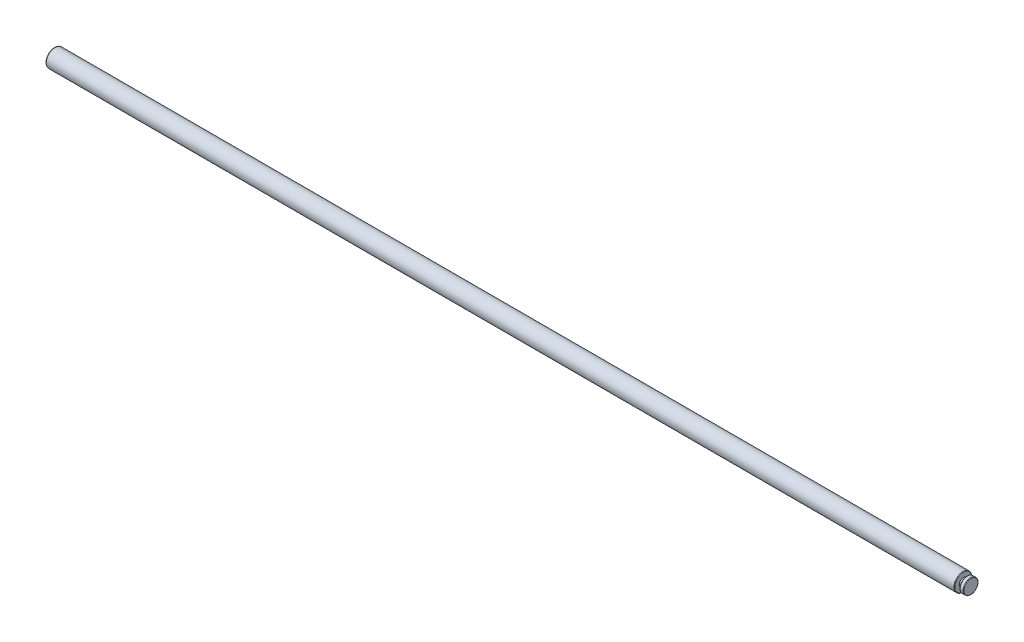
SolidWorks part; units mm, degrees
ref_plane "Front Plane" through (0, 0, 0) normal (0, 0, 1) x (1, 0, 0)
ref_plane "Top Plane" through (0, 0, 0) normal (0, 1, 0) x (1, 0, 0)
ref_plane "Right Plane" through (0, 0, 0) normal (1, 0, 0) x (0, 0, -1)
sketch "Sketch1" plane through (0, 0, 0) normal (0, 0, 1) x (1, 0, 0)
  line L0 (0, 34.9364) -> (0, -34.4273) construction
  line L1 (-72.6727, 0) -> (73.8182, 0) construction
  line L2 (177, 6.5441) -> (177, -8.583) construction
  line L3 (-180, 0) -> (180, 0)
  line L4 (-180, 0) -> (-180, 3.5)
  line L5 (-180, 3.5) -> (177, 3.5)
  line L6 (180, 0) -> (180, 2.9)
  line L7 (177, 3.5) -> (177, 1.5)
  line L8 (177, 1.5) -> (178.5, 1.5)
  line L9 (178.5, 1.5) -> (178.5, 2.9)
  line L10 (178.5, 2.9) -> (180, 2.9)
  dimension "D1" = 3.5
  dimension "D2" = 360
  dimension "D3" = 3
  dimension "D4" = 2
  dimension "D5" = 1.5
  dimension "D6" = 1.4
revolve "Revolve1" add sketch "Sketch1" angle 360 about L3
fillet "Fillet1" radius 0.2 1 edges at (177, 0, 3.5)
fillet "Fillet2" radius 0.2 2 edges at (178.5, 0, 2.9) (180, 0, 2.9)
fillet "Fillet3" radius 0.4 1 edges at (-180, 0, 3.5)
